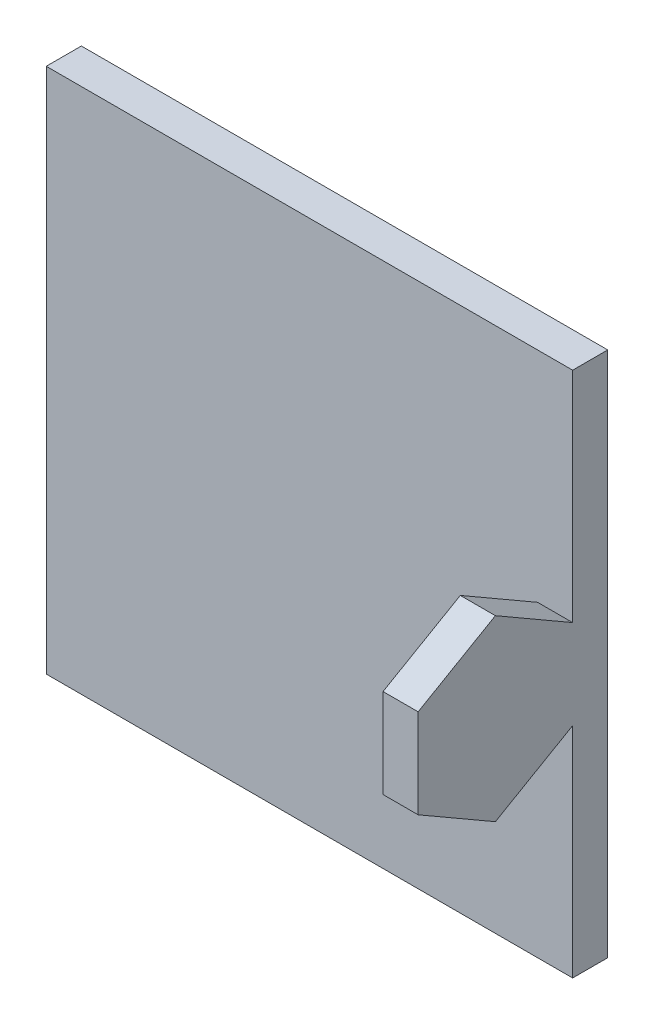
SolidWorks part; units mm, degrees
ref_plane "Front Plane" through (0, 0, 0) normal (0, 0, 1) x (1, 0, 0)
ref_plane "Top Plane" through (0, 0, 0) normal (0, 1, 0) x (1, 0, 0)
ref_plane "Right Plane" through (0, 0, 0) normal (1, 0, 0) x (0, 0, -1)
sketch "Sketch1" plane through (0, 0, 0) normal (0, 0, 1) x (1, 0, 0)
  line L1 (-95.25, 95.25) -> (0, 95.25)
  line L2 (-95.25, 95.25) -> (-95.25, 0)
  line L3 (-95.25, 0) -> (0, 0)
  line L6 (0, 95.25) -> (0, 0)
  point P4 (0, 0)
  point P5 (0, 95.25)
  dimension "D1" = 95.25
  dimension "D2" = 95.25
extrude "Boss-Extrude1" add sketch "Sketch1" along normal blind 6.35 contours L2 L3 L6 L1
sketch "Sketch3" plane through (0, 0, 0) normal (1, 0, 0) x (0, 0, -1)
  line L0 (-6.35, 95.25) -> (-6.35, 0) construction
  line L1 (-6.35, 55.6963) -> (-20.33, 63.7677)
  line L2 (-6.35, 55.6963) -> (-6.35, 39.5537)
  line L3 (-20.33, 63.7677) -> (-34.31, 55.6963)
  line L4 (-34.31, 55.6963) -> (-34.31, 39.5537)
  line L5 (-34.31, 39.5537) -> (-20.33, 31.4823)
  line L6 (-20.33, 31.4823) -> (-6.35, 39.5537)
  point P1 (-20.7092, 36.0904)
  point P2 (-43.1766, 25.0573)
  point P10 (0, 0)
  point P11 (-34.3501, 33.0814)
  point P12 (-34.31, 56.6521)
  point P14 (-6.35, 47.625)
  dimension "D1" = 120
  dimension "D2" = 120
  dimension "D3" = 47.625
extrude "Boss-Extrude2" add sketch "Sketch3" against normal blind 6.35
